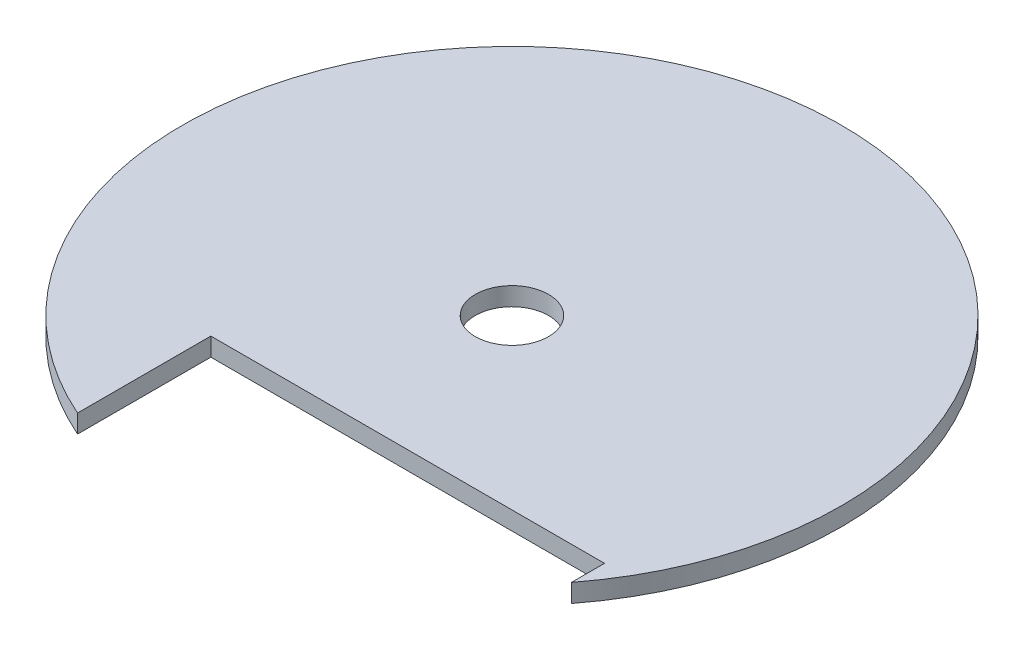
SolidWorks part; units mm, degrees
ref_plane "Front Plane" through (0, 0, 0) normal (0, 0, 1) x (1, 0, 0)
ref_plane "Top Plane" through (0, 0, 0) normal (0, 1, 0) x (1, 0, 0)
ref_plane "Right Plane" through (0, 0, 0) normal (1, 0, 0) x (0, 0, -1)
sketch "Sketch1" plane through (0, 0, 0) normal (0, 1, 0) x (1, 0, 0)
  circle A0 centre (0, 0) radius 36
  circle A1 centre (0, 0) radius 4
  dimension "D1" = 8
  dimension "D2" = 72
extrude "Boss-Extrude1" add sketch "Sketch1" along normal blind 2
sketch "Sketch2" plane through (0, 2, 0) normal (0, 1, 0) x (1, 0, 0)
  line L0 (0, 0) -> (7, 0) construction
  line L1 (7, 0) -> (7, -39.8905) construction
  line L2 (7, -39.8905) -> (0, 0) construction
  line L3 (-14.5, -61.3905) -> (28.5, -61.3905)
  line L4 (-14.5, -61.3905) -> (-14.5, -18.3905)
  line L5 (-14.5, -18.3905) -> (28.5, -18.3905)
  line L6 (28.5, -61.3905) -> (28.5, -18.3905)
  line L7 (-14.5, -61.3905) -> (28.5, -18.3905) construction
  line L8 (-14.5, -18.3905) -> (28.5, -61.3905) construction
  dimension "D1" = 43
  dimension "D2" = 43
  dimension "D3" = 40.5
  dimension "D4" = 7
extrude "Cut-Extrude1" cut sketch "Sketch2" against normal through all
